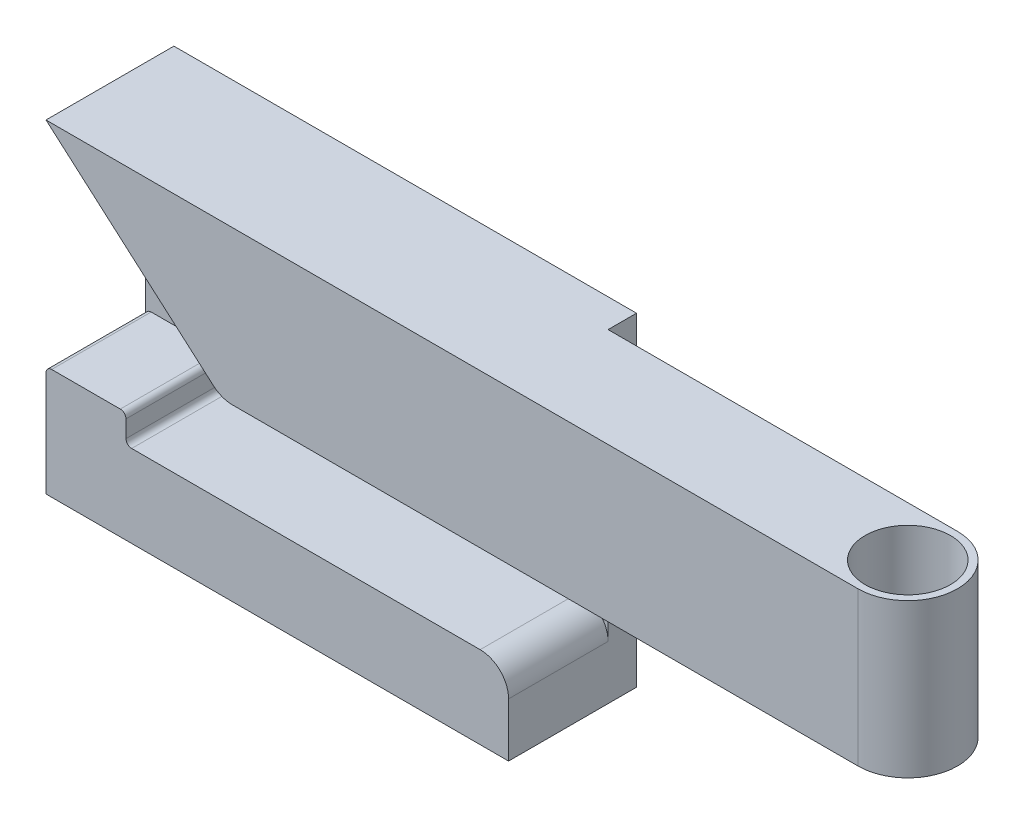
SolidWorks part; units mm, degrees
ref_plane "Front Plane" through (0, 0, 0) normal (0, 0, 1) x (1, 0, 0)
ref_plane "Top Plane" through (0, 0, 0) normal (0, 1, 0) x (1, 0, 0)
ref_plane "Right Plane" through (0, 0, 0) normal (1, 0, 0) x (0, 0, -1)
sketch "Sketch1" plane through (0, 0, 0) normal (0, 0, 1) x (1, 0, 0)
  line L1 (285.667, 30.4211) -> (61.7712, 30.4211)
  line L2 (61.7712, 30.4211) -> (0, 84.4273)
  line L3 (28.1359, -0.5789) -> (162.7321, -0.5789)
  line L6 (0, 9.4211) -> (28.1359, 9.4211)
  line L7 (28.1359, -0.5789) -> (28.1359, 9.4211)
  line L10 (0, 0) -> (0, -29.5338)
  line L11 (0, -29.5338) -> (162.7321, -29.5338)
  line L12 (162.7321, -29.5338) -> (162.7321, -0.5789)
  line L13 (0, 0) -> (0, 9.4211)
  line L14 (0, 84.4273) -> (285.667, 84.4273)
  line L17 (285.667, 84.4273) -> (285.667, 30.4211)
  point P3 (0, 0)
  point P4 (-6.1652, 84.4273)
  point P11 (54.9328, 34.4821)
  point P14 (394.6315, 70.0982)
  point P16 (61.7712, 30.4211)
  dimension "D1" = 31
  dimension "D2" = 10
extrude "Boss-Extrude1" add sketch "Sketch1" along normal blind 35
sketch "Sketch2" plane through (0, 0, 0) normal (0, 0, -1) x (-1, 0, 0)
  line L1 (0, 84.4273) -> (-162.7321, 84.4273)
  line L2 (0, 84.4273) -> (0, -29.5338)
  line L3 (0, -29.5338) -> (-162.7321, -29.5338)
  line L4 (-162.7321, 84.4273) -> (-162.7321, -29.5338)
extrude "Boss-Extrude2" add sketch "Sketch2" along normal blind 10
sketch "Sketch3" plane through (0, 84.4273, 0) normal (0, 1, 0) x (1, 0, 0)
  circle A0 centre (285.667, -17.5) radius 17.5
  dimension "D2" = 35
extrude "Boss-Extrude3" add sketch "Sketch3" against normal up to surface (54.0061 mm away) up to face at (171.5217, 30.4211, 14)
sketch "Sketch4" plane through (0, 84.4273, 0) normal (0, 1, 0) x (1, 0, 0)
  arc A0 (285.667, -35) -> (285.667, 0) centre (285.667, -17.5) ccw construction
  arc A1 (285.667, -35) -> (285.667, 0) centre (285.667, -17.5) ccw construction
  circle A4 centre (285.667, -17.5) radius 15
  dimension "D1" = 30
extrude "Cut-Extrude2" cut sketch "Sketch4" against normal up to next
fillet "Fillet1" radius 2 3 edges at (28.1359, -0.5789, 17.5) (0, 9.4211, 17.5) (28.1359, 9.4211, 17.5)
fillet "Fillet2" radius 10 2 edges at (162.7321, -0.5789, 17.5) (61.7712, 30.4211, 17.5)
